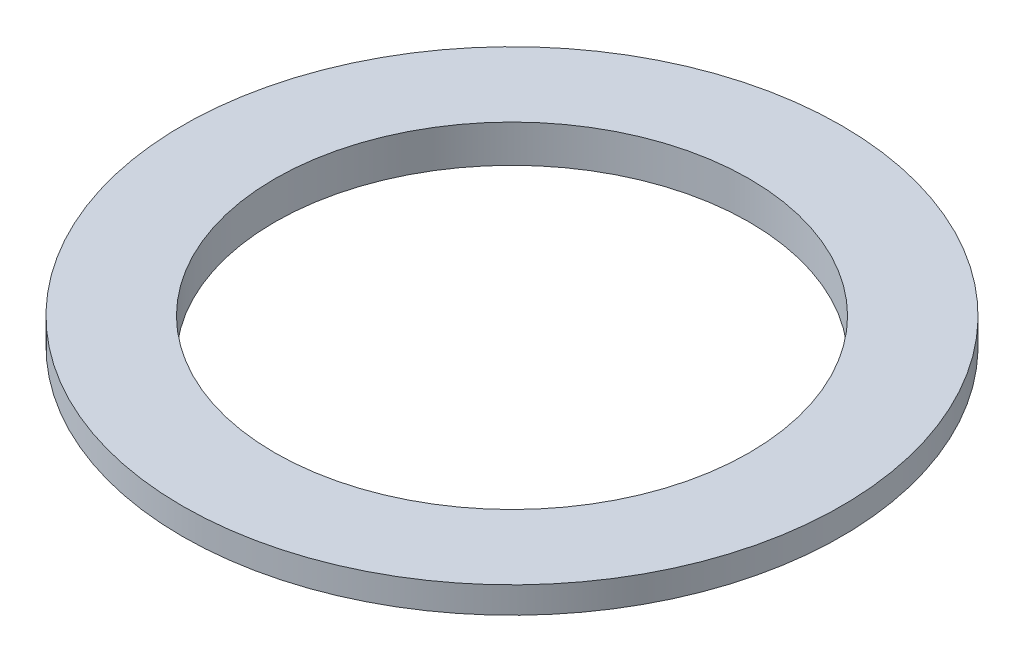
SolidWorks part; units mm, degrees
ref_plane "Front" through (0, 0, 0) normal (0, 0, 1) x (1, 0, 0)
ref_plane "Top" through (0, 0, 0) normal (0, 1, 0) x (1, 0, 0)
ref_plane "Right" through (0, 0, 0) normal (1, 0, 0) x (0, 0, -1)
sketch "Sketch1" plane through (0, 0, 0) normal (0, 1, 0) x (1, 0, 0)
  circle A0 centre (0, 0) radius 138.0507
  circle A1 centre (0, 0) radius 114.3
extrude "Boss-Extrude1" add sketch "Sketch1" along normal blind 5.35
sketch "Sketch2" plane through (0, 5.35, 0) normal (0, 1, 0) x (1, 0, 0)
  circle A0 centre (0, 0) radius 158.75
  circle A2 centre (0, 0) radius 114.3
extrude "Boss-Extrude2" add sketch "Sketch2" along normal blind 12.7
